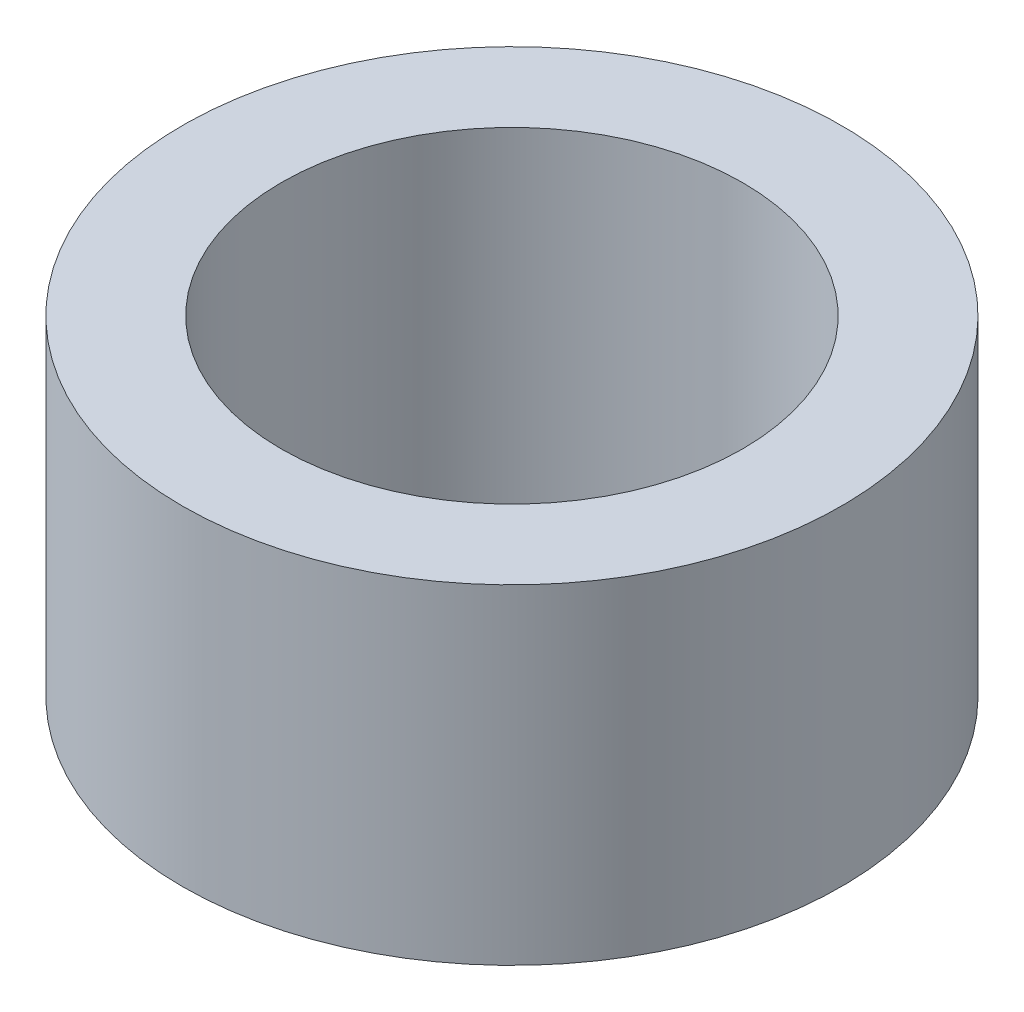
SolidWorks part; units mm, degrees
material "ABS"
ref_plane "正面" through (0, 0, 0) normal (0, 0, 1) x (1, 0, 0)
ref_plane "平面" through (0, 0, 0) normal (0, 1, 0) x (1, 0, 0)
ref_plane "右側面" through (0, 0, 0) normal (1, 0, 0) x (0, 0, -1)
sketch "ｽｹｯﾁ1" plane through (0, 0, 0) normal (0, 1, 0) x (1, 0, 0)
  circle A0 centre (0, 0) radius 2.1
  circle A1 centre (0, 0) radius 3
  dimension "D1" = 6
  dimension "D2" = 4.2
extrude "ﾎﾞｽ - 押し出し1" add sketch "ｽｹｯﾁ1" along normal blind 3
